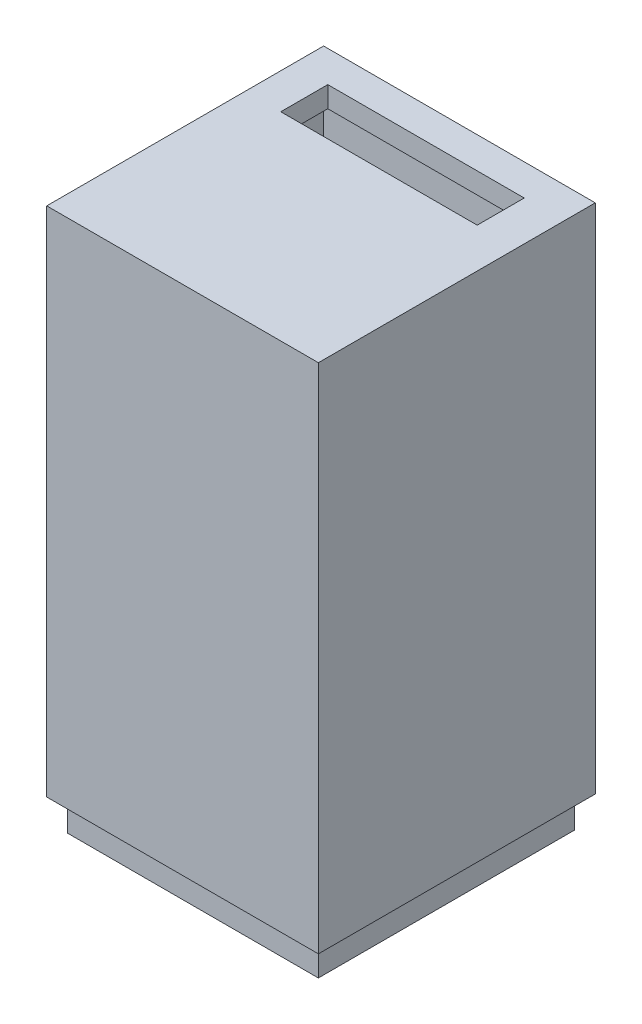
SolidWorks part; units mm, degrees
ref_plane "前视基准面" through (0, 0, 0) normal (0, 0, 1) x (1, 0, 0)
ref_plane "上视基准面" through (0, 0, 0) normal (0, 1, 0) x (1, 0, 0)
ref_plane "右视基准面" through (0, 0, 0) normal (1, 0, 0) x (0, 0, -1)
sketch "草图2" plane through (0, 0, 0) normal (0, 0, 1) x (1, 0, 0)
  line L1 (0, 0) -> (22, 0)
  line L2 (0, 0) -> (0, 47)
  line L3 (0, 47) -> (22, 47)
  line L4 (22, 0) -> (22, 47)
  line L5 (-2, 49) -> (24, 49)
  line L6 (-2, 49) -> (-2, -2)
  line L7 (-2, -2) -> (24, -2)
  line L8 (24, 49) -> (24, -2)
  dimension "D1" = 47
  dimension "D2" = 22
  dimension "D3" = 26
  dimension "D4" = 2
  dimension "D5" = 51
  dimension "D6" = 2
extrude "凸台-拉伸1" add sketch "草图2" along normal blind 17 and the other way blind 5.5
sketch "草图3" plane through (0, 0, -5.5) normal (0, 0, -1) x (-1, 0, 0)
  line L1 (-24, 49) -> (2, 49)
  line L2 (-24, 49) -> (-24, -2)
  line L3 (-24, -2) -> (2, -2)
  line L4 (2, 49) -> (2, -2)
extrude "凸台-拉伸2" add sketch "草图3" along normal blind 2
sketch "草图4" plane through (0, 0, 17) normal (0, 0, 1) x (1, 0, 0)
  line L1 (22, 47) -> (0, 47) construction
  line L2 (1.4, 47) -> (20.2, 47)
  line L3 (1.4, 47) -> (1.4, 49)
  line L4 (1.4, 49) -> (20.2, 49)
  line L5 (20.2, 47) -> (20.2, 49)
  line L6 (24, 49) -> (-2, 49) construction
  line L7 (24, -2) -> (24, 49) construction
  line L8 (-2, 49) -> (24, 49)
  line L9 (-2, 49) -> (-2, 47)
  line L10 (-2, 47) -> (24, 47)
  line L11 (24, 49) -> (24, 47)
  dimension "D1" = 3.4
  dimension "D2" = 3.8
extrude "切除-拉伸1" cut sketch "草图4" against normal blind 4.5 from offset 17 contours L4 L5 L2 L3 offset against normal yes
sketch "草图5" plane through (0, 0, 17) normal (0, 0, 1) x (1, 0, 0)
  line L1 (-2, 49) -> (24, 49)
  line L2 (-2, 49) -> (-2, -2)
  line L3 (-2, -2) -> (24, -2)
  line L4 (24, 49) -> (24, -2)
extrude "凸台-拉伸3" add sketch "草图5" along normal blind 2
sketch "草图6" plane through (0, -2, 0) normal (0, -1, 0) x (1, 0, 0)
  line L1 (-2, 19) -> (24, 19)
  line L2 (-2, 19) -> (-2, -7.5)
  line L3 (-2, -7.5) -> (24, -7.5)
  line L4 (24, 19) -> (24, -7.5)
extrude "切除-拉伸2" cut sketch "草图6" against normal blind 2
sketch "草图7" plane through (0, 0, 0) normal (0, -1, 0) x (1, 0, 0)
  line L1 (0, 17) -> (22, 17)
  line L2 (0, 17) -> (0, -5.5)
  line L3 (0, -5.5) -> (22, -5.5)
  line L4 (22, 17) -> (22, -5.5)
  line L5 (-1, 18.0009) -> (23, 18.0009)
  line L6 (-1, 18.0009) -> (-1, -6.4991)
  line L7 (-1, -6.4991) -> (23, -6.4991)
  line L8 (23, 18.0009) -> (23, -6.4991)
  dimension "D1" = 22
  dimension "D2" = 22.5
  dimension "D3" = 24
  dimension "D4" = 24.5
  dimension "D5" = 1.0009
  dimension "D6" = 1
extrude "凸台-拉伸4" add sketch "草图7" along normal blind 3
